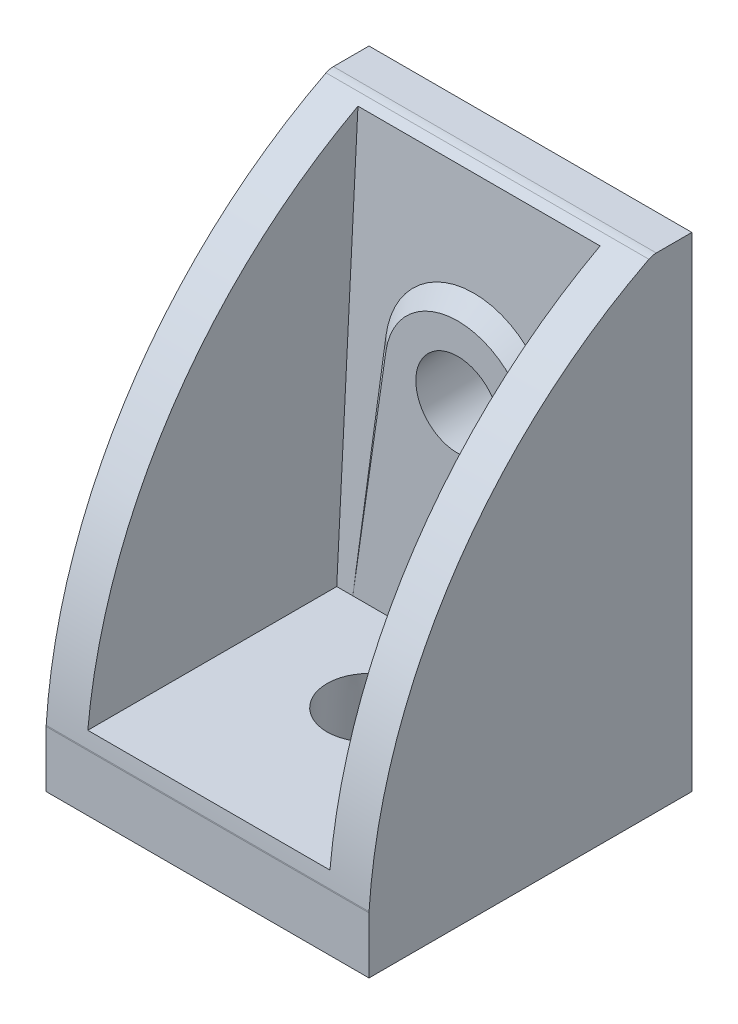
SolidWorks part; units mm, degrees
ref_plane "Front Plane" through (0, 0, 0) normal (0, 0, 1) x (1, 0, 0)
ref_plane "Top Plane" through (0, 0, 0) normal (0, 1, 0) x (1, 0, 0)
ref_plane "Right Plane" through (0, 0, 0) normal (1, 0, 0) x (0, 0, -1)
ref_plane "Plane1" through (0, 0, 0) normal (1, 0, 0) x (0, 0, -1)
sketch "Sketch1" plane through (0, 0, 0) normal (1, 0, 0) x (0, 0, -1)
  line L0 (-20, 0) -> (0, 0)
  line L1 (0, 0) -> (0, 30)
  line L2 (0, 30) -> (-2.2048, 30)
  line L3 (-20, 3.4921) -> (-20, 0)
  arc A0 (-2.2048, 30) -> (-2.6607, 29.89) centre (-2.2048, 29) ccw
  arc A1 (-2.6607, 29.89) -> (-19.9977, 3.5593) centre (11.93, 1.41) ccw
  arc A2 (-19.9977, 3.5593) -> (-20, 3.4921) centre (-19, 3.4921) ccw
extrude "Boss-Extrude1" add sketch "Sketch1" along normal blind 20
ref_plane "Plane2" through (10, 0, 0) normal (1, 0, 0) x (0, 0, -1)
sketch "Sketch2" plane through (10, 0, 0) normal (1, 0, 0) x (0, 0, -1)
  line L0 (-20, 4.5) -> (-4.5, 4.5)
  line L1 (-4.5, 4.5) -> (-3.1636, 30)
  line L2 (-3.1636, 30) -> (-20, 30)
  line L3 (-20, 30) -> (-20, 4.5)
extrude "Cut-Extrude1" cut sketch "Sketch2" against normal blind 7.5 and the other way blind 7.5
ref_plane "Plane3" through (10, 0, 0) normal (1, 0, 0) x (0, 0, -1)
sketch "Sketch3" plane through (10, 0, 0) normal (1, 0, 0) x (0, 0, -1)
  line L0 (-0.5, 23.5) -> (1, 24.366)
  line L1 (1, 24.366) -> (1, 25.634)
  line L2 (1, 25.634) -> (-0.5, 26.5)
  line L3 (-0.5, 26.5) -> (-0.5, 23.5)
extrude "Boss-Extrude2" add sketch "Sketch3" against normal blind 3 and the other way blind 3
ref_plane "Plane4" through (10, 0, 0) normal (1, 0, 0) x (0, 0, -1)
sketch "Sketch4" plane through (10, 0, 0) normal (1, 0, 0) x (0, 0, -1)
  line L0 (-0.5, 4) -> (1, 4.866)
  line L1 (1, 4.866) -> (1, 12.134)
  line L2 (1, 12.134) -> (-0.5, 13)
  line L3 (-0.5, 13) -> (-0.5, 4)
extrude "Boss-Extrude3" add sketch "Sketch4" against normal blind 3 and the other way blind 3
ref_plane "Plane5" through (0, 0, 4.5) normal (0, 0, 1) x (1, 0, 0)
sketch "Sketch5" plane through (0, 0, 4.5) normal (0, 0, 1) x (1, 0, 0)
  line L0 (3.4955, 4.5) -> (16.5045, 4.5)
  line L1 (16.5045, 4.5) -> (14.4534, 18.6457)
  line L2 (5.5466, 18.6457) -> (3.4955, 4.5)
  arc A0 (14.4534, 18.6457) -> (5.5466, 18.6457) centre (10, 18) ccw
extrude "Boss-Extrude4" add sketch "Sketch5" against normal blind 2 draft 45 draft outward yes
ref_plane "Plane6" through (0, 0.5, 0) normal (0, 1, 0) x (1, 0, 0)
sketch "Sketch6" plane through (0, 0.5, 0) normal (0, 1, 0) x (1, 0, 0)
  line L0 (7.075, -12.925) -> (12.925, -12.925)
  line L1 (12.925, -12.925) -> (12.925, -7.075)
  line L2 (12.925, -7.075) -> (7.075, -7.075)
  line L3 (7.075, -7.075) -> (7.075, -12.925)
extrude "Boss-Extrude5" add sketch "Sketch6" against normal blind 1.5 draft 6
ref_plane "Plane7" through (0, 0, 0) normal (0, 1, 0) x (1, 0, 0)
sketch "Sketch7" plane through (0, 0, 0) normal (0, 1, 0) x (1, 0, 0)
  line L0 (7.075, -9.165) -> (7.075, -10.835)
  line L1 (7.075, -10.835) -> (9.165, -10.835)
  line L2 (9.165, -10.835) -> (9.165, -12.925)
  line L3 (9.165, -12.925) -> (10.835, -12.925)
  line L4 (10.835, -12.925) -> (10.835, -10.835)
  line L5 (10.835, -10.835) -> (12.925, -10.835)
  line L6 (12.925, -10.835) -> (12.925, -9.165)
  line L7 (12.925, -9.165) -> (10.835, -9.165)
  line L8 (10.835, -9.165) -> (10.835, -7.075)
  line L9 (10.835, -7.075) -> (9.165, -7.075)
  line L10 (9.165, -7.075) -> (9.165, -9.165)
  line L11 (9.165, -9.165) -> (7.075, -9.165)
extrude "Cut-Extrude2" cut sketch "Sketch7" against normal blind 1 draft 6 draft outward yes
ref_plane "Plane8" through (10, 0, 0) normal (1, 0, 0) x (0, 0, -1)
sketch "Sketch8" plane through (10, 0, 0) normal (1, 0, 0) x (0, 0, -1)
  line L0 (-4.5, 18) -> (-4.5, 20.6)
  line L1 (-4.5, 20.6) -> (0, 20.8358)
  line L2 (0, 20.8358) -> (0, 18)
  line L3 (0, 18) -> (-4.5, 18)
  line L4 (0, 18) -> (-4.5, 18) construction
revolve "Cut-Revolve1" cut sketch "Sketch8" angle 360 about L4
ref_plane "Plane9" through (10, 0, 0) normal (1, 0, 0) x (0, 0, -1)
sketch "Sketch9" plane through (10, 0, 0) normal (1, 0, 0) x (0, 0, -1)
  line L0 (-10, 4.5) -> (-7.4, 4.5)
  line L1 (-7.4, 4.5) -> (-7.1118, -1)
  line L2 (-7.1118, -1) -> (-10, -1)
  line L3 (-10, -1) -> (-10, 4.5)
  line L4 (-10, -1) -> (-10, 4.5) construction
revolve "Cut-Revolve2" cut sketch "Sketch9" angle 360 about L4
